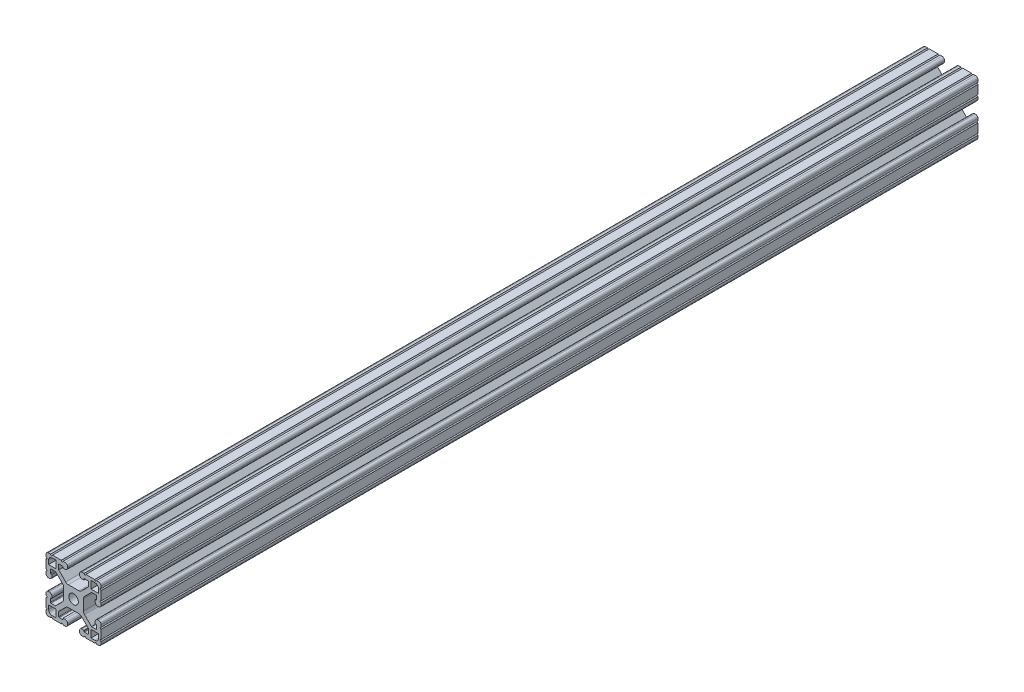
SolidWorks part; units mm, degrees
ref_plane "Front Plane" through (0, 0, 0) normal (0, 0, 1) x (1, 0, 0)
ref_plane "Top Plane" through (0, 0, 0) normal (0, 1, 0) x (1, 0, 0)
ref_plane "Right Plane" through (0, 0, 0) normal (1, 0, 0) x (0, 0, -1)
sketch "Sketch1" plane through (0, 0, 0) normal (0, 0, 1) x (1, 0, 0)
  line L0 (0, -19.05) -> (0, 19.05) construction
  line L1 (19.05, 0) -> (-19.05, 0) construction
  line L2 (4.064, 19.05) -> (-4.064, 19.05) construction
  line L3 (0, -6.858) -> (0, 6.858) construction
  line L4 (-4.064, 19.05) -> (-4.064, 14.986) construction
  line L5 (19.05, -10.287) -> (19.05, 10.287) construction
  line L6 (0, -3.302) -> (0, 3.302) construction
  point P4 (0, 0)
  point P8 (0, 0)
  point P11 (0, 19.05)
  point P14 (0, 0)
  point P18 (19.05, 0)
  point P21 (0, 0)
  dimension "Rail Width" = 38.1
  dimension "Rail Height" = 38.1
  dimension "T-Slot Width" = 8.128
  dimension "Thickness" = 4.064
  dimension "Opening Width" = 20.574
  dimension "Center Hole Diameter" = 6.604
  dimension "Slot Depth" = 12.192
sketch "Sketch2" plane through (0, 0, 0) normal (1, 0, 0) x (0, 0, -1)
  line L0 (-303.2125, 0) -> (303.2125, 0) construction
  line L1 (0, 19.05) -> (0, -19.05) construction
  line L2 (-25.4, 19.05) -> (25.4, 19.05) construction
  line L4 (3048, -19.05) -> (-3048, -19.05) construction
  point P0 (252.4125, 0)
  point P3 (-252.4125, 0)
  point P4 (0, 0)
  dimension "D1" = 50.8
  dimension "Rep Length" = 606.425
  dimension "D2" = 50.8
  dimension "Length Range [Min]" = 50.8
  dimension "Length Range [Max]" = 6096
sketch "Sketch3" plane through (0, 0, 0) normal (0, 0, 1) x (1, 0, 0)
  line L1 (19.05, -19.05) -> (-19.05, -19.05)
  line L2 (19.05, -19.05) -> (19.05, 19.05)
  line L3 (19.05, 19.05) -> (-19.05, 19.05)
  line L4 (-19.05, -19.05) -> (-19.05, 19.05)
  line L5 (19.05, -19.05) -> (-19.05, 19.05) construction
  line L6 (19.05, 19.05) -> (-19.05, -19.05) construction
  point P0 (0, 0)
extrude "Boss-Extrude1" add sketch "Sketch3" along normal up to vertex (303.2125 mm away) and the other way up to vertex (303.2125 mm away) up to point (0, 0, 303.2125) other way up to point (0, 0, -303.2125)
sketch "Sketch4" plane through (0, 0, 303.2125) normal (0, 0, 1) x (1, 0, 0)
  line L4 (4.064, 14.986) -> (4.064, 19.05)
  line L5 (7.239, 14.986) -> (4.064, 14.986)
  line L6 (19.05, 0) -> (-19.05, 0) construction
  line L7 (4.7027, 6.858) -> (-4.7027, 6.858)
  line L8 (-4.7027, 6.858) -> (-10.287, 12.4423)
  line L37 (-19.05, 19.05) -> (-19.05, -19.05) construction
  line L38 (-19.05, -19.05) -> (19.05, -19.05) construction
  line L39 (-10.287, 12.4423) -> (-10.287, 16.002)
  line L40 (-10.287, 16.002) -> (-7.239, 16.002)
  line L41 (-7.239, 16.002) -> (-7.239, 14.986)
  line L42 (-7.239, 14.986) -> (-4.064, 14.986)
  line L43 (-4.064, 14.986) -> (-4.064, 19.05)
  line L44 (-4.064, 19.05) -> (4.064, 19.05)
  line L45 (0, 19.05) -> (0, 0) construction
  line L46 (-19.05, 19.05) -> (0, 0) construction
  line L47 (7.239, 16.002) -> (7.239, 14.986)
  line L48 (10.287, 16.002) -> (7.239, 16.002)
  line L49 (10.287, 12.4423) -> (10.287, 16.002)
  line L50 (4.7027, 6.858) -> (10.287, 12.4423)
  line L51 (-19.05, 0) -> (19.05, 0) construction
  line L52 (4.7027, -6.858) -> (10.287, -12.4423)
  line L53 (10.287, -12.4423) -> (10.287, -16.002)
  line L54 (10.287, -16.002) -> (7.239, -16.002)
  line L55 (7.239, -16.002) -> (7.239, -14.986)
  line L56 (-4.064, -19.05) -> (4.064, -19.05)
  line L57 (-4.064, -14.986) -> (-4.064, -19.05)
  line L58 (-7.239, -14.986) -> (-4.064, -14.986)
  line L59 (-7.239, -16.002) -> (-7.239, -14.986)
  line L60 (-10.287, -16.002) -> (-7.239, -16.002)
  line L61 (-10.287, -12.4423) -> (-10.287, -16.002)
  line L62 (-4.7027, -6.858) -> (-10.287, -12.4423)
  line L63 (4.7027, -6.858) -> (-4.7027, -6.858)
  line L64 (7.239, -14.986) -> (4.064, -14.986)
  line L65 (4.064, -14.986) -> (4.064, -19.05)
  line L66 (-6.858, -4.7027) -> (-12.4423, -10.287)
  line L67 (-12.4423, -10.287) -> (-16.002, -10.287)
  line L68 (-16.002, -10.287) -> (-16.002, -7.239)
  line L69 (-16.002, -7.239) -> (-14.986, -7.239)
  line L70 (-19.05, 4.064) -> (-19.05, -4.064)
  line L71 (-14.986, 4.064) -> (-19.05, 4.064)
  line L72 (-14.986, 7.239) -> (-14.986, 4.064)
  line L73 (-16.002, 7.239) -> (-14.986, 7.239)
  line L74 (-16.002, 10.287) -> (-16.002, 7.239)
  line L75 (-12.4423, 10.287) -> (-16.002, 10.287)
  line L76 (-6.858, 4.7027) -> (-12.4423, 10.287)
  line L77 (-6.858, -4.7027) -> (-6.858, 4.7027)
  line L78 (-14.986, -7.239) -> (-14.986, -4.064)
  line L79 (-14.986, -4.064) -> (-19.05, -4.064)
  line L80 (14.986, -4.064) -> (19.05, -4.064)
  line L81 (14.986, -7.239) -> (14.986, -4.064)
  line L82 (6.858, -4.7027) -> (6.858, 4.7027)
  line L83 (6.858, 4.7027) -> (12.4423, 10.287)
  line L84 (12.4423, 10.287) -> (16.002, 10.287)
  line L85 (16.002, 10.287) -> (16.002, 7.239)
  line L86 (16.002, 7.239) -> (14.986, 7.239)
  line L87 (14.986, 7.239) -> (14.986, 4.064)
  line L88 (14.986, 4.064) -> (19.05, 4.064)
  line L89 (19.05, 4.064) -> (19.05, -4.064)
  line L90 (16.002, -7.239) -> (14.986, -7.239)
  line L91 (16.002, -10.287) -> (16.002, -7.239)
  line L92 (12.4423, -10.287) -> (16.002, -10.287)
  line L93 (6.858, -4.7027) -> (12.4423, -10.287)
  line L94 (19.05, -19.05) -> (19.05, 19.05) construction
  line L95 (12.065, 17.272) -> (17.272, 17.272)
  line L96 (12.065, 17.272) -> (12.065, 12.065)
  line L97 (12.065, 12.065) -> (17.272, 12.065)
  line L98 (17.272, 17.272) -> (17.272, 12.065)
  line L99 (19.05, 19.05) -> (-19.05, 19.05) construction
  line L100 (17.272, -17.272) -> (17.272, -12.065)
  line L101 (12.065, -17.272) -> (17.272, -17.272)
  line L102 (12.065, -17.272) -> (12.065, -12.065)
  line L103 (12.065, -12.065) -> (17.272, -12.065)
  line L104 (-17.272, 17.272) -> (-17.272, 12.065)
  line L105 (-12.065, 12.065) -> (-17.272, 12.065)
  line L106 (-12.065, 17.272) -> (-12.065, 12.065)
  line L107 (-12.065, 17.272) -> (-17.272, 17.272)
  line L108 (-12.065, -12.065) -> (-17.272, -12.065)
  line L109 (-12.065, -17.272) -> (-12.065, -12.065)
  line L110 (-12.065, -17.272) -> (-17.272, -17.272)
  line L111 (-17.272, -17.272) -> (-17.272, -12.065)
  circle A5 centre (0, 0) radius 3.302
  point P21 (0, 6.858)
  point P23 (0, -6.858)
  point P38 (-6.858, 0)
  point P53 (6.858, 0)
  dimension "D1" = 20.574
  dimension "D2" = 3.048
  dimension "D3" = 3.048
  dimension "D4" = 3.048
  dimension "D5" = 1.778
  dimension "D6" = 1.778
  dimension "D7" = 1.778
extrude "Cut-Extrude1" cut sketch "Sketch4" against normal through all
sketch "Sketch5" plane through (0, 0, 303.2125) normal (0, 0, 1) x (1, 0, 0)
  line L4 (-4.064, 19.05) -> (-19.05, 19.05) construction
  line L26 (-19.05, 19.05) -> (-19.05, 4.064) construction
  line L27 (-15.875, 19.05) -> (-14.605, 19.05)
  line L28 (-8.509, 19.05) -> (-7.239, 19.05)
  line L29 (-19.05, 15.875) -> (-19.05, 14.605)
  line L30 (-19.05, 8.509) -> (-19.05, 7.239)
  line L31 (8.509, 19.05) -> (7.239, 19.05)
  line L32 (15.875, 19.05) -> (14.605, 19.05)
  line L33 (19.05, 15.875) -> (19.05, 14.605)
  line L34 (19.05, 8.509) -> (19.05, 7.239)
  line L35 (19.05, -8.509) -> (19.05, -7.239)
  line L36 (19.05, -15.875) -> (19.05, -14.605)
  line L37 (15.875, -19.05) -> (14.605, -19.05)
  line L38 (8.509, -19.05) -> (7.239, -19.05)
  line L39 (-8.509, -19.05) -> (-7.239, -19.05)
  line L40 (-15.875, -19.05) -> (-14.605, -19.05)
  line L41 (-19.05, -15.875) -> (-19.05, -14.605)
  line L42 (-19.05, -8.509) -> (-19.05, -7.239)
  line L43 (19.05, 19.05) -> (4.064, 19.05) construction
  line L44 (19.05, 4.064) -> (19.05, 19.05) construction
  line L48 (-14.986, 4.064) -> (-19.05, 4.064) construction
  line L49 (-4.064, 14.986) -> (-4.064, 19.05) construction
  arc A8 (-15.875, 19.05) -> (-14.605, 19.05) centre (-15.24, 19.05) ccw
  arc A9 (-8.509, 19.05) -> (-7.239, 19.05) centre (-7.874, 19.05) ccw
  arc A10 (-19.05, 14.605) -> (-19.05, 15.875) centre (-19.05, 15.24) ccw
  arc A11 (-19.05, 7.239) -> (-19.05, 8.509) centre (-19.05, 7.874) ccw
  arc A12 (7.239, 19.05) -> (8.509, 19.05) centre (7.874, 19.05) ccw
  arc A13 (14.605, 19.05) -> (15.875, 19.05) centre (15.24, 19.05) ccw
  arc A14 (19.05, 15.875) -> (19.05, 14.605) centre (19.05, 15.24) ccw
  arc A15 (19.05, 8.509) -> (19.05, 7.239) centre (19.05, 7.874) ccw
  arc A16 (19.05, -7.239) -> (19.05, -8.509) centre (19.05, -7.874) ccw
  arc A17 (19.05, -14.605) -> (19.05, -15.875) centre (19.05, -15.24) ccw
  arc A18 (15.875, -19.05) -> (14.605, -19.05) centre (15.24, -19.05) ccw
  arc A19 (8.509, -19.05) -> (7.239, -19.05) centre (7.874, -19.05) ccw
  arc A20 (-7.239, -19.05) -> (-8.509, -19.05) centre (-7.874, -19.05) ccw
  arc A21 (-14.605, -19.05) -> (-15.875, -19.05) centre (-15.24, -19.05) ccw
  arc A22 (-19.05, -15.875) -> (-19.05, -14.605) centre (-19.05, -15.24) ccw
  arc A23 (-19.05, -8.509) -> (-19.05, -7.239) centre (-19.05, -7.874) ccw
  dimension "D2" = 0.635
  dimension "D4" = 3.81
  dimension "D5" = 3.81
  dimension "D1" = 3.81
  dimension "D3" = 3.81
  dimension "D7" = 4
extrude "Cut-Extrude2" cut sketch "Sketch5" against normal through all
fillet "Fillet1" radius 2.54 12 edges at (-6.858, 4.7027, 0) (-6.858, -4.7027, 0) (4.7027, -6.858, 0) (-4.7027, -6.858, 0) (6.858, -4.7027, 0) (6.858, 4.7027, 0) (4.7027, 6.858, 0) (-4.7027, 6.858, 0) (-17.272, 17.272, 0) (17.272, 17.272, 0) (17.272, -17.272, 0) (-17.272, -17.272, 0)
fillet "Fillet2" radius 1.778 20 edges at (19.05, -19.05, 0) (19.05, 19.05, 0) (-19.05, -19.05, 0) (-19.05, 19.05, 0) (-14.986, 4.064, 0) (-19.05, 4.064, 0) (-19.05, -4.064, 0) (-14.986, -4.064, 0) (-4.064, -19.05, 0) (-4.064, -14.986, 0) (4.064, -14.986, 0) (4.064, -19.05, 0) (19.05, -4.064, 0) (14.986, -4.064, 0) (19.05, 4.064, 0) (14.986, 4.064, 0) (4.064, 14.986, 0) (4.064, 19.05, 0) (-4.064, 19.05, 0) (-4.064, 14.986, 0)
fillet "Fillet3" radius 0.3969 24 edges at (-14.986, -7.239, 0) (-16.002, -10.287, 0) (-12.4423, -10.287, 0) (-12.4423, 10.287, 0) (-16.002, 7.239, 0) (-16.002, 10.287, 0) (-10.287, 12.4423, 0) (-7.239, 16.002, 0) (-10.287, 16.002, 0) (10.287, 16.002, 0) (7.239, 16.002, 0) (10.287, 12.4423, 0) (16.002, 10.287, 0) (12.4423, 10.287, 0) (16.002, 7.239, 0) (16.002, -7.239, 0) (16.002, -10.287, 0) (12.4423, -10.287, 0) (10.287, -12.4423, 0) (10.287, -16.002, 0) (7.239, -16.002, 0) (-7.239, -16.002, 0) (-10.287, -12.4423, 0) (-10.287, -16.002, 0)
equation "\"D4@Sketch5\"=\"D3@Sketch5\""
equation "\"D5@Sketch5\"=\"D4@Sketch5\""
equation "\"D1@Sketch4\"=\"Opening Width@Sketch1\""
